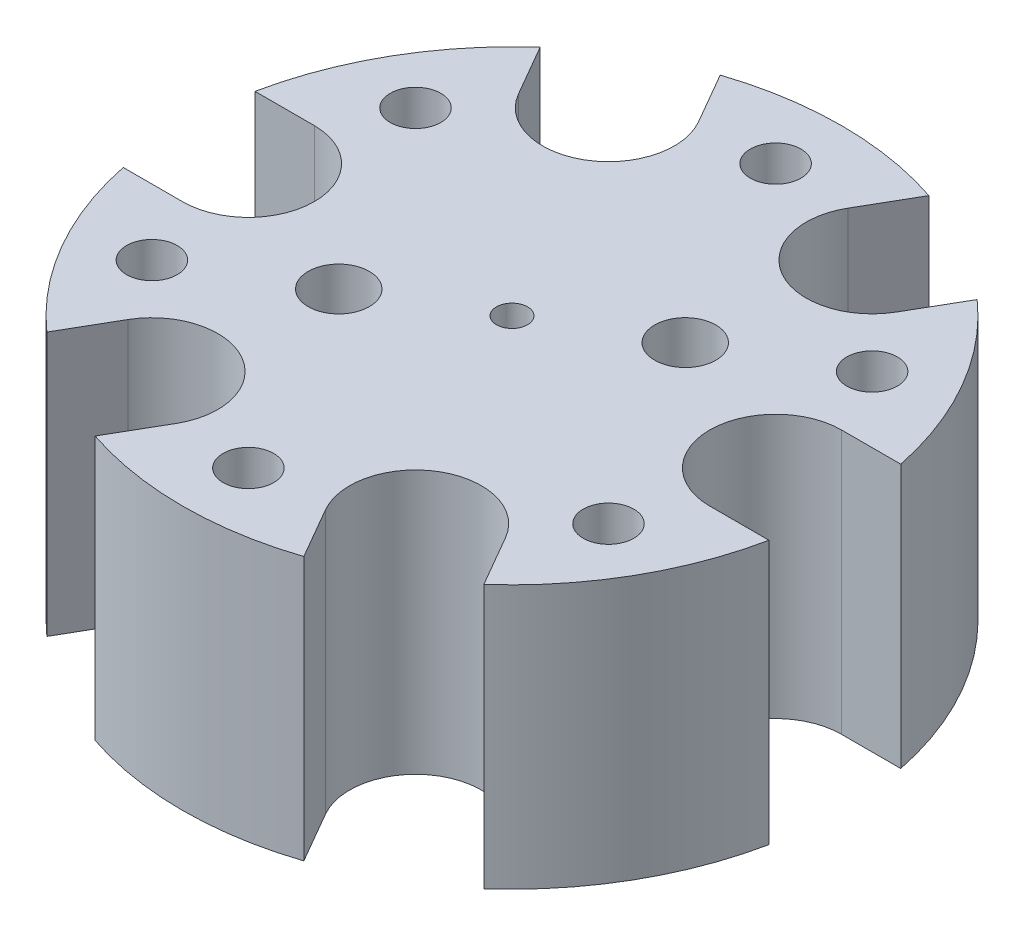
SolidWorks part; units mm, degrees
ref_plane "Front Plane" through (0, 0, 0) normal (0, 0, 1) x (1, 0, 0)
ref_plane "Top Plane" through (0, 0, 0) normal (0, 1, 0) x (1, 0, 0)
ref_plane "Right Plane" through (0, 0, 0) normal (1, 0, 0) x (0, 0, -1)
sketch "Sketch1" plane through (0, 0, 0) normal (0, 1, 0) x (1, 0, 0)
  circle A0 centre (0, 0) radius 15.875
extrude "Boss-Extrude1" add sketch "Sketch1" along normal blind 12.7
sketch "Sketch2" plane through (0, 12.7, 0) normal (0, 1, 0) x (1, 0, 0)
  circle A0 centre (0, 0) radius 0.7493
extrude "Cut-Extrude1" cut sketch "Sketch2" against normal blind 20
sketch "Sketch3" plane through (0, 12.7, 0) normal (0, 1, 0) x (1, 0, 0)
  circle A0 centre (0, 12.7) radius 1.2192
extrude "Cut-Extrude3" cut sketch "Sketch3" against normal through all
sketch "Sketch4" plane through (0, 12.7, 0) normal (0, 1, 0) x (1, 0, 0)
  line L1 (12.7, -3.175) -> (20.9586, -3.175)
  line L2 (12.7, -3.175) -> (12.7, 3.175)
  line L3 (12.7, 3.175) -> (20.9586, 3.175)
  line L4 (20.9586, -3.175) -> (20.9586, 3.175)
  circle A0 centre (12.7, 0) radius 3.175
  circle M8 centre (0, 0) radius 15.875
extrude "Cut-Extrude4" cut sketch "Sketch4" against normal blind 20 contours L2 A0 | L2 A0 | L1 L4 L3 M8 | A0 L3 M8 | A0 L1 M8
sketch "Sketch5" plane through (0, 0, 0) normal (0, -1, 0) x (-1, 0, 0)
  line L1 (-12.7, -3.175) -> (-17.9438, -3.175)
  line L2 (-12.7, -3.175) -> (-12.7, 3.175)
  line L3 (-12.7, 3.175) -> (-17.9438, 3.175)
  line L4 (-17.9438, -3.175) -> (-17.9438, 3.175)
  circle A0 centre (-12.7, 0) radius 3.175
pattern_circular "CirPattern1" count 6 every 60 about axis through (0, 0, 0) along (0, 1, 0) of "Cut-Extrude3", "Cut-Extrude4"
sketch "Sketch6" plane through (0, 0, 0) normal (0, -1, 0) x (1, 0, 0)
  line L3 (0, 0) -> (5.2914, -3.055)
  line L4 (0, 0) -> (-5.2914, 3.055)
hole_wizard "#32 (0.116) Diameter Hole2" positions "Sketch10" profile "Sketch9" hole size "#32" standard "ANSI Inch" end condition through all
sketch "Sketch10" plane through (0, 0, 0) normal (0, -1, 0) x (-1, 0, 0)
  point P0 (5.2914, -3.055)
  point P3 (-5.2914, 3.055)
sketch "Sketch9" plane through (-5.2914, 0, 3.055) normal (1, 0, 0) x (0, 0, -1)
  line L0 (0, 0) -> (0, 12.7)
  line L1 (0, 12.7) -> (1.4732, 12.7)
  line L2 (1.4732, 12.7) -> (1.4732, 0)
  line L5 (1.4732, 0) -> (0, 0)
  line L11 (0, -6.35) -> (0, 107.95) construction
  dimension "Thru Hole Dia." = 2.9464
  dimension "Thru Hole Depth" = 12.7
